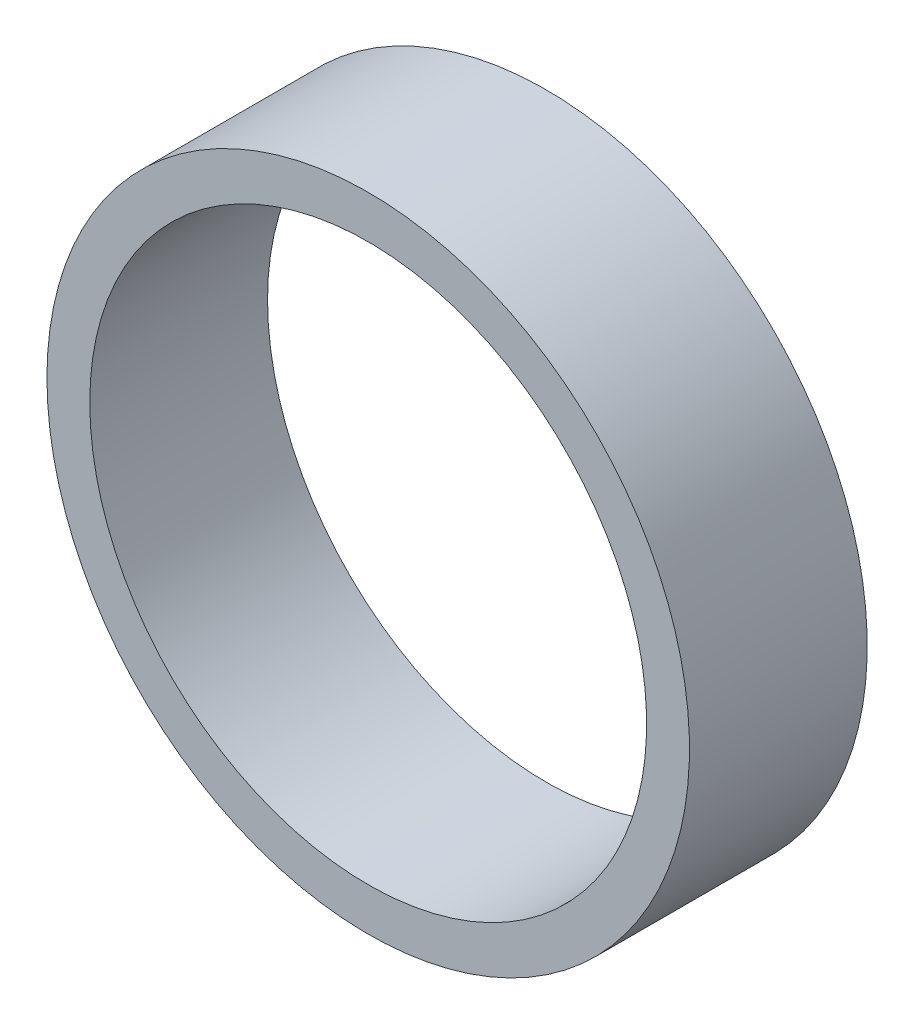
SolidWorks part; units mm, degrees
ref_plane "Front Plane" through (0, 0, 0) normal (0, 0, 1) x (1, 0, 0)
ref_plane "Top Plane" through (0, 0, 0) normal (0, 1, 0) x (1, 0, 0)
ref_plane "Right Plane" through (0, 0, 0) normal (1, 0, 0) x (0, 0, -1)
sketch "Sketch1" plane through (0, 0, 0) normal (0, 0, 1) x (1, 0, 0)
  circle A0 centre (0, 0) radius 7.5
  circle A1 centre (0, 0) radius 6.5
  dimension "D1" = 15
  dimension "D2" = 1
extrude "Boss-Extrude1" add sketch "Sketch1" along normal blind 4.15 contours A1
